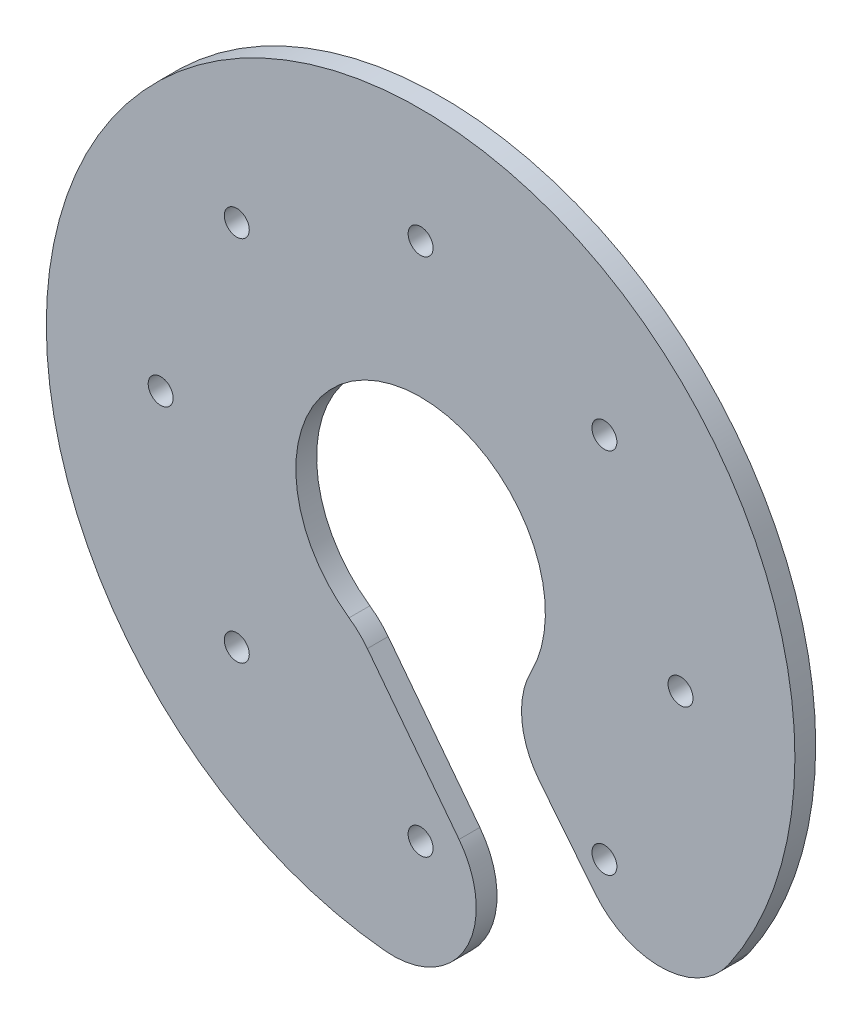
SolidWorks part; units mm, degrees
ref_plane "Front Plane" through (0, 0, 0) normal (0, 0, 1) x (1, 0, 0)
ref_plane "Top Plane" through (0, 0, 0) normal (0, 1, 0) x (1, 0, 0)
ref_plane "Right Plane" through (0, 0, 0) normal (1, 0, 0) x (0, 0, -1)
sketch "Sketch1" plane through (0, 0, 0) normal (0, 0, 1) x (1, 0, 0)
  circle A0 centre (0, 0) radius 90
  dimension "D1" = 180
extrude "Boss-Extrude1" add sketch "Sketch1" along normal blind 5
sketch "Sketch2" plane through (0, 0, 5) normal (0, 0, 1) x (1, 0, 0)
  line L0 (69.7683, -87.0816) -> (45.9714, -105.3493)
  line L1 (-14.9208, -26.0263) -> (45.9714, -105.3493)
  line L2 (69.7683, -87.0816) -> (18.7577, -23.4125)
  arc A0 (18.7577, -23.4125) -> (-14.9208, -26.0263) centre (0, 0) ccw
  dimension "D1" = 60
  dimension "D2" = 100
  dimension "D3" = 30
extrude "Cut-Extrude1" cut sketch "Sketch2" against normal blind 44
sketch "Sketch3" plane through (0, 0, 5) normal (0, 0, 1) x (1, 0, 0)
  circle A0 centre (62.5, 0) radius 3
  circle A1 centre (44.1942, -44.1942) radius 3
  circle A3 centre (0, -62.5) radius 3
  circle A4 centre (-44.1942, -44.1942) radius 3
  circle A5 centre (-62.5, 0) radius 3
  circle A6 centre (-44.1942, 44.1942) radius 3
  circle A7 centre (0, 62.5) radius 3
  circle A8 centre (44.1942, 44.1942) radius 3
  point P20 (0, 0)
  dimension "D3" = 8
extrude "Cut-Extrude2" cut sketch "Sketch3" against normal blind 129
fillet "Fillet1" radius 20 4 edges at (-14.9208, -26.0263, 2.5) (30.1865, -84.7866, 2.5) (56.2732, -70.2376, 2.5) (18.7577, -23.4125, 2.5)
